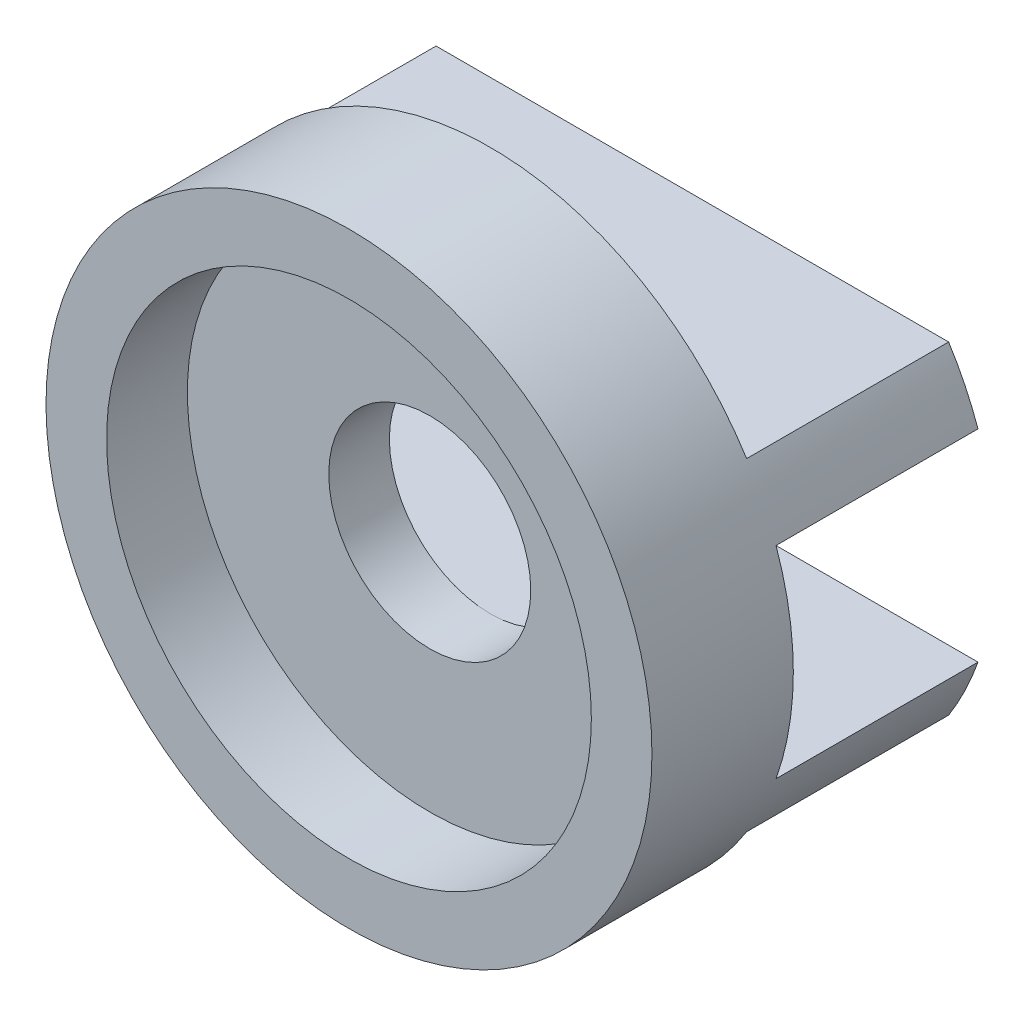
SolidWorks part; units mm, degrees
ref_plane "Alzado" through (0, 0, 0) normal (0, 0, 1) x (1, 0, 0)
ref_plane "Planta" through (0, 0, 0) normal (0, 1, 0) x (1, 0, 0)
ref_plane "Vista lateral" through (0, 0, 0) normal (1, 0, 0) x (0, 0, -1)
sketch "Croquis1" plane through (0, 0, 0) normal (0, 0, 1) x (1, 0, 0)
  circle A0 centre (0, 0) radius 75
extrude "Saliente-Extruir1" add sketch "Croquis1" along normal blind 15
sketch "Croquis2" plane through (0, 0, 0) normal (0, 0, -1) x (-1, 0, 0)
  line L0 (0, 0) -> (0, 25)
  line L1 (0, 0) -> (0, -25)
  line L2 (-70.7107, -25) -> (70.7107, -25)
  line L3 (0, 25) -> (-70.7107, 25)
  line L4 (-70.7107, 25) -> (70.7107, 25)
  line L5 (0, 25) -> (0, 40)
  line L6 (-63.4429, 40) -> (63.4429, 40)
  line L7 (0, 0) -> (-13.3847, 0)
  line L8 (-63.4429, -40) -> (63.4429, -40)
  line L9 (0, -25) -> (0, -40)
  line L10 (-70.7107, -25) -> (70.7107, -25)
  line L11 (0, -25) -> (-70.7107, -25)
  circle A0 centre (0, 0) radius 75 construction
  arc A1 (-63.4429, 40) -> (-70.7107, 25) centre (0, 0) ccw
  arc A2 (63.4429, 40) -> (70.7107, 25) centre (0, 0) cw
  arc A3 (63.4429, -40) -> (70.7107, -25) centre (0, 0) ccw
  arc A4 (-63.4429, -40) -> (-70.7107, -25) centre (0, 0) cw
  circle M9 centre (0, 0) radius 75
extrude "Saliente-Extruir2" add sketch "Croquis2" along normal blind 50 contours L6 L3 L5 M9 | L6 L5 L4 M9 | L2 L9 L8 M9 | L9 L2 L8 M9
sketch "Croquis3" plane through (0, 0, 15) normal (0, 0, 1) x (1, 0, 0)
  circle A0 centre (0, 0) radius 60
  circle A1 centre (0, 0) radius 75
extrude "Saliente-Extruir3" add sketch "Croquis3" along normal blind 20
sketch "Croquis4" plane through (0, 0, 15) normal (0, 0, 1) x (1, 0, 0)
  circle A0 centre (0, 0) radius 25
extrude "Cortar-Extruir1" cut sketch "Croquis4" against normal blind 20
